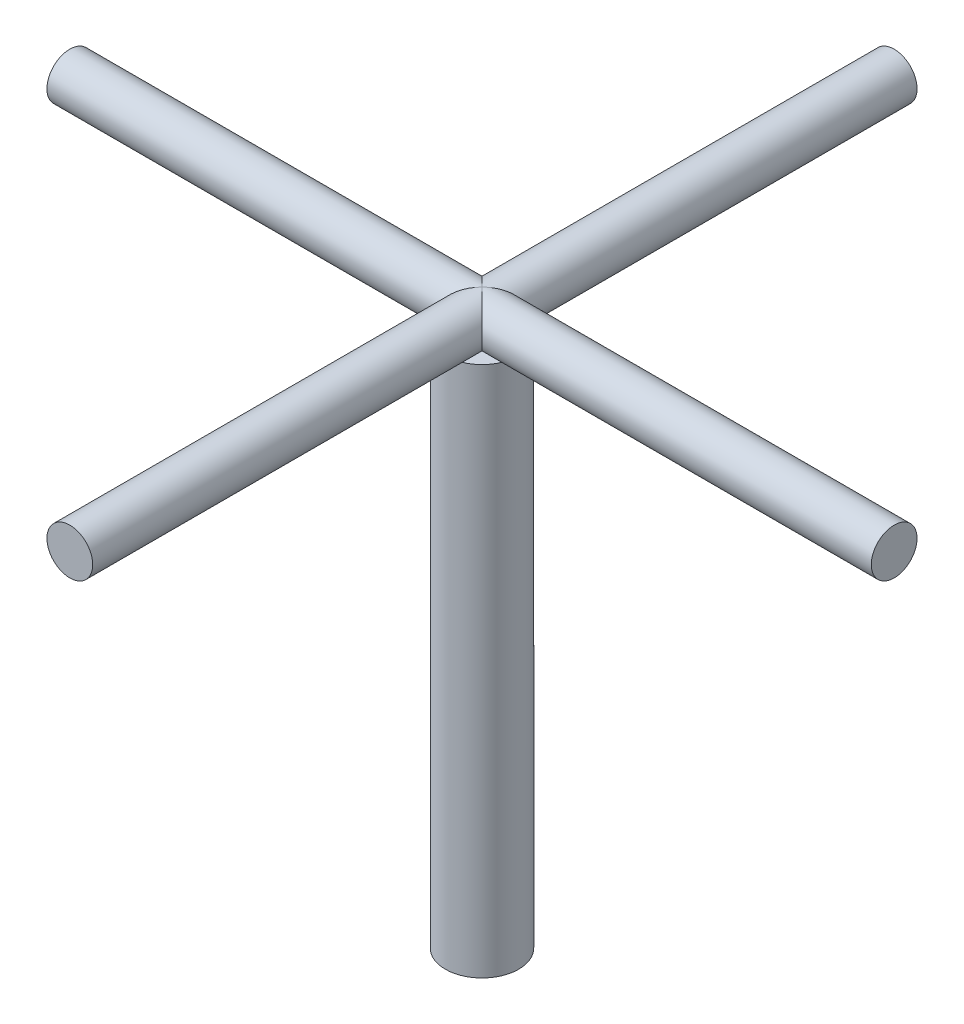
SolidWorks part; units mm, degrees
material "Balsa"
ref_plane "Front Plane" through (0, 0, 0) normal (0, 0, 1) x (1, 0, 0)
ref_plane "Top Plane" through (0, 0, 0) normal (0, 1, 0) x (1, 0, 0)
ref_plane "Right Plane" through (0, 0, 0) normal (1, 0, 0) x (0, 0, -1)
sketch "Sketch1" plane through (0, 0, 0) normal (0, 1, 0) x (1, 0, 0)
  circle A0 centre (0, 0) radius 40
  dimension "D1" = 80
extrude "trunk" add sketch "Sketch1" along normal blind 580
sketch "Sketch2" plane through (0, 0, 0) normal (1, 0, 0) x (0, 0, -1)
  line L0 (0, 0) -> (0, 600) construction
  line L1 (0, 600) -> (-450, 600)
  line L2 (0, 600) -> (-266.3909, 600) construction
  dimension "D1" = 600
  dimension "D2" = 0
  dimension "D3" = 450
sweep "branch base" add path "Sketch2" circular profile diameter 50 parameters "D3"=50
pattern_circular "branches" count 4 over 360 about axis through (0, 0, 0) along (0, 1, 0) of "branch base"
